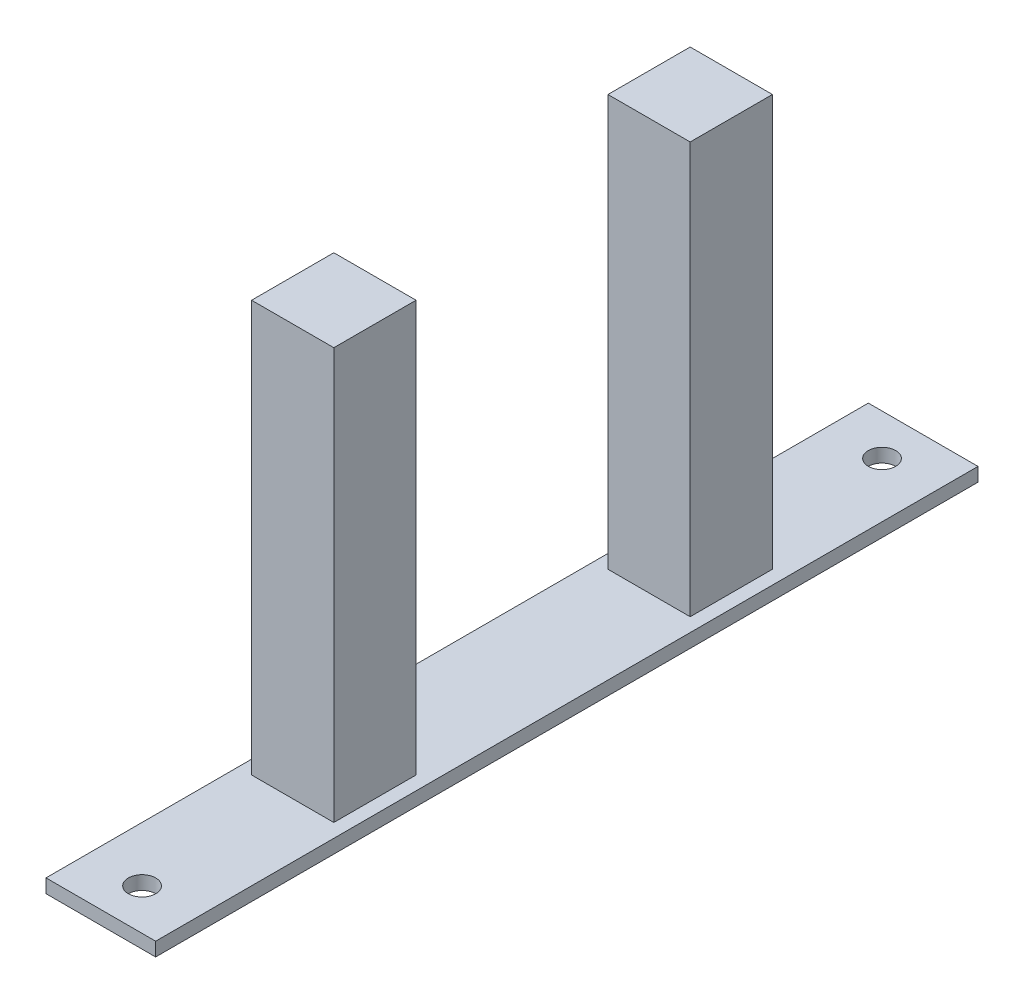
SolidWorks part; units mm, degrees
ref_plane "Front Plane" through (0, 0, 0) normal (0, 0, 1) x (1, 0, 0)
ref_plane "Top Plane" through (0, 0, 0) normal (0, 1, 0) x (1, 0, 0)
ref_plane "Right Plane" through (0, 0, 0) normal (1, 0, 0) x (0, 0, -1)
sketch "Sketch1" plane through (0, 0, 0) normal (0, 1, 0) x (1, 0, 0)
  line L0 (0, -55) -> (0, 55) construction
  line L1 (-20, 150) -> (20, 150)
  line L2 (-20, 150) -> (-20, -150)
  line L3 (-20, -150) -> (20, -150)
  line L4 (20, 150) -> (20, -150)
  line L5 (-20, 150) -> (20, -150) construction
  line L6 (-20, -150) -> (20, 150) construction
  line L7 (-55, 0) -> (55, 0) construction
  point P0 (0, 0)
  dimension "D1" = 40
  dimension "D2" = 300
extrude "Boss-Extrude1" add sketch "Sketch1" along normal blind 5
sketch "Sketch2" plane through (0, 5, 0) normal (0, 1, 0) x (1, 0, 0)
  line L0 (0, -55) -> (0, 55) construction
  line L1 (-15, 80) -> (15, 80)
  line L2 (-15, 80) -> (-15, 50)
  line L3 (-15, 50) -> (15, 50)
  line L4 (15, 80) -> (15, 50)
  line L5 (-15, 80) -> (15, 50) construction
  line L6 (-15, 50) -> (15, 80) construction
  line L7 (20, 150) -> (-20, 150) construction
  line L8 (-20, -150) -> (20, -150) construction
  line L9 (-15, -50) -> (15, -50)
  line L10 (-15, -50) -> (-15, -80)
  line L11 (-15, -80) -> (15, -80)
  line L12 (15, -50) -> (15, -80)
  line L13 (-15, -50) -> (15, -80) construction
  line L14 (-15, -80) -> (15, -50) construction
  point P0 (0, 65)
  point P9 (0, -65)
  point P14 (15, -65)
  dimension "D1" = 30
  dimension "D2" = 30
  dimension "D3" = 70
  dimension "D4" = 30
  dimension "D5" = 30
  dimension "D6" = 70
extrude "Boss-Extrude2" add sketch "Sketch2" along normal blind 150
sketch "Sketch3" plane through (0, 5, 0) normal (0, 1, 0) x (1, 0, 0)
  line L0 (20, 150) -> (-20, 150) construction
  line L1 (-20, -150) -> (20, -150) construction
  circle A0 centre (-0.0227, 135) radius 5
  circle A1 centre (0.0308, -135) radius 7.5
  dimension "D1" = 10
  dimension "D3" = 15
  dimension "D2" = 15
  dimension "D4" = 15
extrude "Cut-Extrude2" cut sketch "Sketch3" against normal up to vertex (5 mm away) contours A0
sketch "Sketch6" plane through (0, 5, 0) normal (0, 1, 0) x (1, 0, 0)
  line L0 (-20, -150) -> (20, -150) construction
  circle A0 centre (0.0362, -135) radius 5
  dimension "D1" = 10
  dimension "D2" = 15
extrude "Cut-Extrude3" cut sketch "Sketch6" against normal up to vertex (5 mm away)
